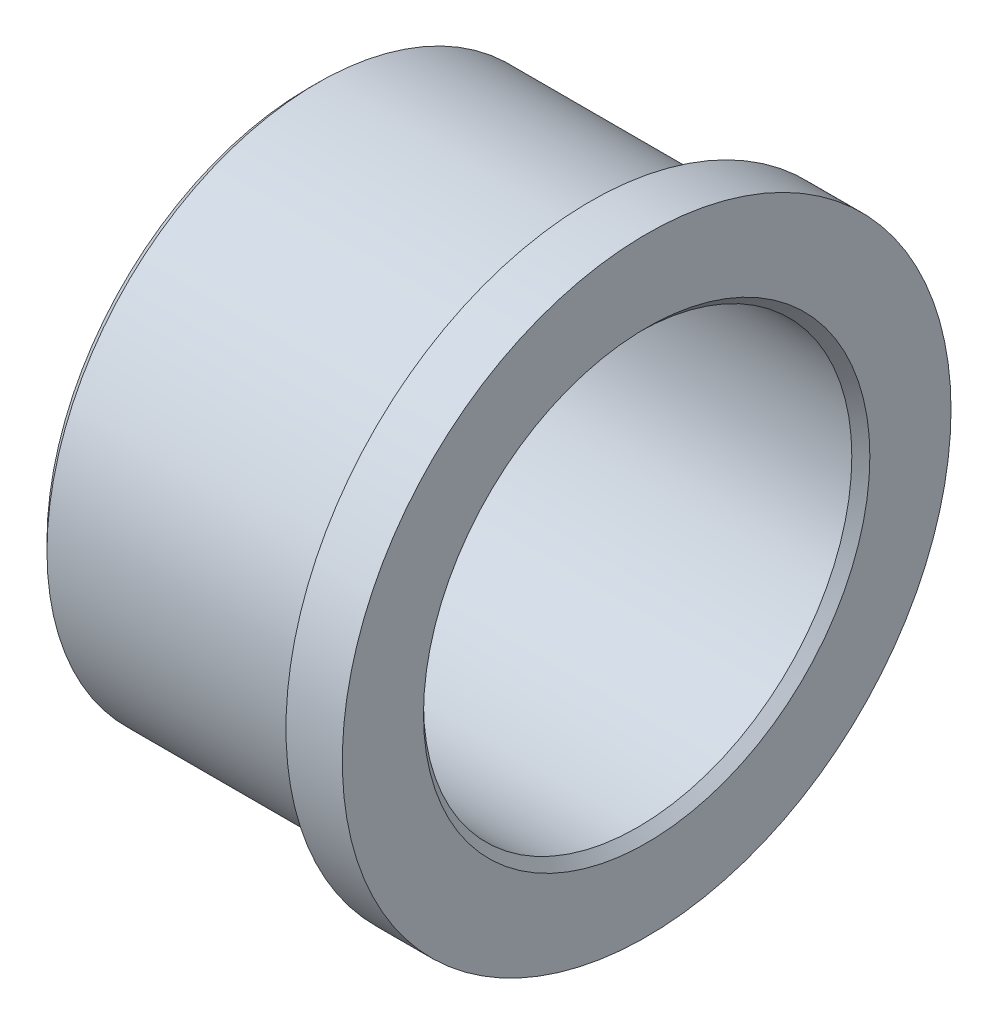
SolidWorks part; units mm, degrees
material "2.1030 (CuSn8P)"
ref_plane "Ebene vorne" through (0, 0, 0) normal (0, 0, 1) x (1, 0, 0)
ref_plane "Ebene oben" through (0, 0, 0) normal (0, 1, 0) x (1, 0, 0)
ref_plane "Ebene rechts" through (0, 0, 0) normal (1, 0, 0) x (0, 0, -1)
ref_axis "A_Drehachse" through (6.5, 0, 0) along (-1, 0, 0)
sketch "Skizze1" plane through (0, 0, 0) normal (0, 0, 1) x (1, 0, 0)
  line L0 (-2, 24) -> (-25, 24)
  line L1 (0, -29.7) -> (0, 29.7) construction
  line L2 (0, 25.3691) -> (0, 27)
  line L3 (0, 27) -> (5, 27)
  line L4 (5, 27) -> (5, 19)
  line L5 (5, 19) -> (-25, 19)
  line L6 (-25, 19) -> (-25, 24)
  line L7 (0, 25.3691) -> (0, 23.8)
  line L8 (0, 23.8) -> (-2, 23.8)
  line L9 (-2, 23.8) -> (-2, 24)
  line L10 (55, 0) -> (-55, 0) construction
  point P14 (-2, 23.9)
  dimension "D1" = 27
  dimension "D2" = 24
  dimension "D3" = 19
  dimension "D4" = 5
  dimension "D5" = 30
  dimension "D6" = 0.2
  dimension "D7" = 2
revolve "Rotation1" add sketch "Skizze1" angle 360 about axis through (6.5, 0, 0) along (-1, 0, 0)
chamfer "Fase1" distance 0.8 angle 45 3 edges at (5, 0, -19) (-25, 0, -24) (-25, 0, -19)
